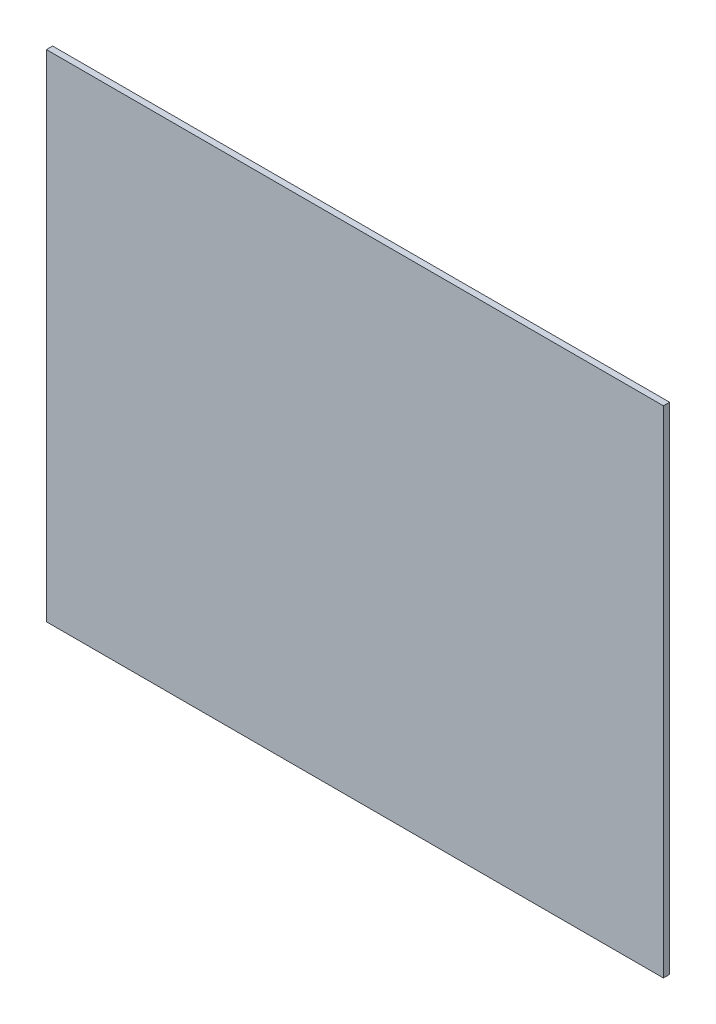
SolidWorks part; units mm, degrees
ref_plane "前视基准面" through (0, 0, 0) normal (0, 0, 1) x (1, 0, 0)
ref_plane "上视基准面" through (0, 0, 0) normal (0, 1, 0) x (1, 0, 0)
ref_plane "右视基准面" through (0, 0, 0) normal (1, 0, 0) x (0, 0, -1)
sketch "草图1" plane through (0, 0, 0) normal (0, 0, 1) x (1, 0, 0)
  line L1 (-92.443, 75.7769) -> (7.157, 75.7769)
  line L2 (-92.443, 75.7769) -> (-92.443, -4.2231)
  line L3 (-92.443, -4.2231) -> (7.157, -4.2231)
  line L4 (7.157, 75.7769) -> (7.157, -4.2231)
  dimension "D1" = 80
  dimension "D2" = 99.6
extrude "凸台-拉伸1" add sketch "草图1" along normal blind 1 contours L1 L4 L3 L2
